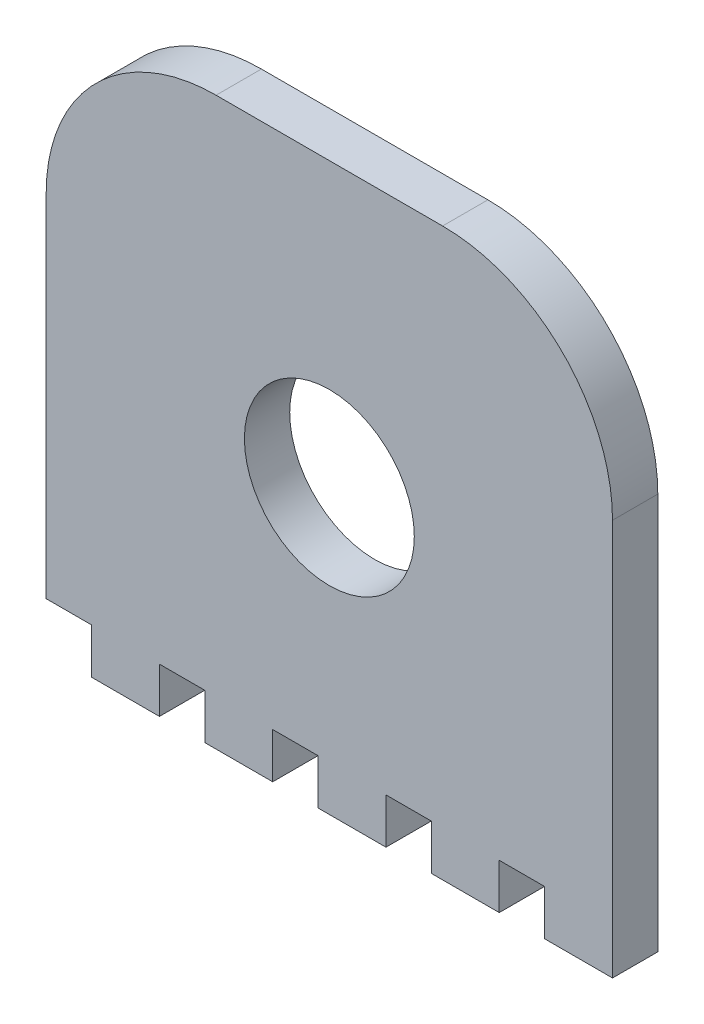
SolidWorks part; units mm, degrees
ref_plane "Front Plane" through (0, 0, 0) normal (0, 0, 1) x (1, 0, 0)
ref_plane "Top Plane" through (0, 0, 0) normal (0, 1, 0) x (1, 0, 0)
ref_plane "Right Plane" through (0, 0, 0) normal (1, 0, 0) x (0, 0, -1)
sketch "Sketch1" plane through (0, 0, 0) normal (0, 0, 1) x (1, 0, 0)
  line L1 (-25, -25) -> (25, -25)
  line L2 (-25, -25) -> (-25, 25)
  line L3 (-25, 25) -> (25, 25)
  line L4 (25, -25) -> (25, 25)
  line L5 (-25, -25) -> (25, 25) construction
  line L6 (-25, 25) -> (25, -25) construction
  point P0 (0, 0)
  dimension "D1" = 50
  dimension "D2" = 50
extrude "Boss-Extrude1" add sketch "Sketch1" along normal blind 4
sketch "Sketch2" plane through (0, 0, 0) normal (0, 0, 1) x (1, 0, 0)
  line L0 (-25, -25) -> (25, -25) construction
  line L1 (-25, -25) -> (-21, -25)
  line L2 (-25, -25) -> (-25, -21)
  line L3 (-25, -21) -> (-21, -21)
  line L4 (-21, -25) -> (-21, -21)
  line L9 (-15, -25) -> (-11, -25)
  line L10 (-15, -25) -> (-15, -21)
  line L11 (-15, -21) -> (-11, -21)
  line L12 (-11, -25) -> (-11, -21)
  line L14 (-5, -25) -> (-1, -25)
  line L15 (-5, -25) -> (-5, -21)
  line L16 (-5, -21) -> (-1, -21)
  line L17 (-1, -25) -> (-1, -21)
  line L18 (5, -25) -> (9, -25)
  line L19 (5, -25) -> (5, -21)
  line L20 (5, -21) -> (9, -21)
  line L21 (9, -25) -> (9, -21)
  line L22 (15, -25) -> (19, -25)
  line L23 (15, -25) -> (15, -21)
  line L24 (15, -21) -> (19, -21)
  line L25 (19, -25) -> (19, -21)
  dimension "D1" = 4
  dimension "D2" = 4
  dimension "D3" = 4
  dimension "D4" = 4
  dimension "D5" = 4
  dimension "D6" = 4
  dimension "D7" = 4
  dimension "D8" = 4
  dimension "D9" = 4
  dimension "D10" = 4
  dimension "D13" = 10
  dimension "D14" = 10
  dimension "D15" = 10
  dimension "D16" = 10
extrude "Cut-Extrude1" cut sketch "Sketch2" along normal blind 4
sketch "Sketch3" plane through (0, 0, 0) normal (0, 0, 1) x (1, 0, 0)
  circle A0 centre (0, 0) radius 7.5
  dimension "D1" = 25
  dimension "D3" = 15
  dimension "D2" = 25
extrude "Cut-Extrude2" cut sketch "Sketch3" along normal blind 4
fillet "Fillet1" radius 15 2 edges at (25, 25, 2) (-25, 25, 2)
